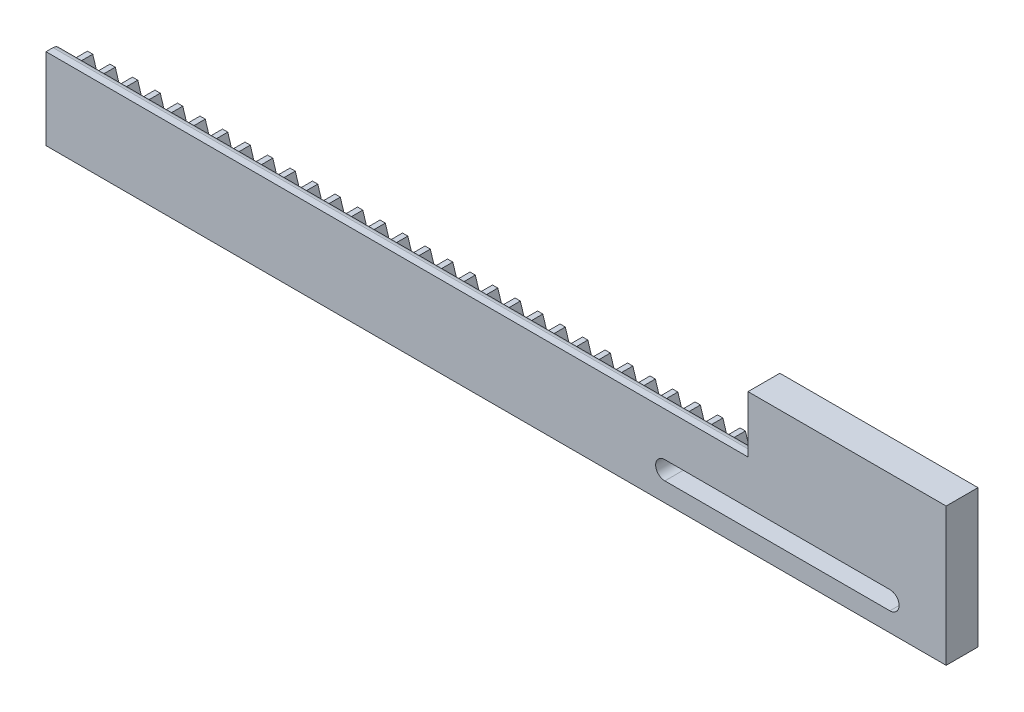
SolidWorks part; units mm, degrees
material "ABS"
ref_plane "Front Plane" through (0, 0, 0) normal (0, 0, 1) x (1, 0, 0)
ref_plane "Top Plane" through (0, 0, 0) normal (0, 1, 0) x (1, 0, 0)
ref_plane "Right Plane" through (0, 0, 0) normal (1, 0, 0) x (0, 0, -1)
sketch "Sketch4" plane through (0, 0, 0) normal (1, 0, 0) x (0, 0, -1)
  line L0 (0, 0) -> (-4.5, 0)
  line L1 (-4.5, 0) -> (-4.5, 11.5)
  line L2 (-4.5, 11.5) -> (-2.5, 11.5)
  line L3 (-2.5, 11.5) -> (-2.5, 8)
  line L4 (-2.5, 8) -> (0, 8)
  line L5 (0, 8) -> (0, 0)
  dimension "D1" = 4.5
  dimension "D2" = 2
  dimension "D3" = 8
  dimension "D4" = 11.5
extrude "Boss-Extrude3" add sketch "Sketch4" along normal blind 127.2
sketch "Sketch6" plane through (0, 0, 4.5) normal (0, 0, 1) x (1, 0, 0)
  line L0 (87.45, 4) -> (119.25, 4) construction
  line L1 (87.45, 5.3) -> (119.25, 5.3)
  line L2 (87.45, 2.7) -> (119.25, 2.7)
  line L3 (127.2, 0) -> (0, 0) construction
  line L6 (127.2, 0) -> (127.2, 8) construction
  arc A0 (87.45, 5.3) -> (87.45, 2.7) centre (87.45, 4) ccw
  arc A1 (119.25, 2.7) -> (119.25, 5.3) centre (119.25, 4) ccw
  point P2 (103.35, 4)
  point P11 (0, 4.2218)
  dimension "D4" = 1.3
  dimension "D1" = 4
  dimension "D2" = 7.95
  dimension "D3" = 31.8
extrude "Cut-Extrude1" cut sketch "Sketch6" against normal through all
sketch "Sketch8" plane through (0, 0, 0) normal (0, 0, -1) x (-1, 0, 0)
  line L0 (-94.9527, 8) -> (-94.3277, 10)
  line L1 (-127.2, 8) -> (0, 8) construction
  line L2 (-94.3277, 10) -> (-93.5777, 10)
  line L3 (-93.5777, 10) -> (-92.9527, 8)
  line L4 (-92.9527, 8) -> (-94.9527, 8)
  dimension "D1" = 2
  dimension "D2" = 2
  dimension "D3" = 0.75
extrude "Boss-Extrude5" add sketch "Sketch8" against normal up to next
pattern_linear "LPattern3" count 30 spacing 3.18 along (-1, 0, 0) count 11 spacing 3.18 along (1, 0, 0) of "Boss-Extrude5"
fillet "Fillet2" radius 1 1 edges at (63.6, 11.5, 2.5)
sketch "Sketch9" plane through (0, 11.5, 0) normal (0, 1, 0) x (1, 0, 0)
  line L1 (127.2, -4.5) -> (99.2, -4.5)
  line L2 (127.2, -4.5) -> (127.2, 0)
  line L3 (127.2, 0) -> (99.2, 0)
  line L4 (99.2, -4.5) -> (99.2, 0)
  dimension "D1" = 28
extrude "Boss-Extrude6" add sketch "Sketch9" along normal blind 8 and the other way up to next
